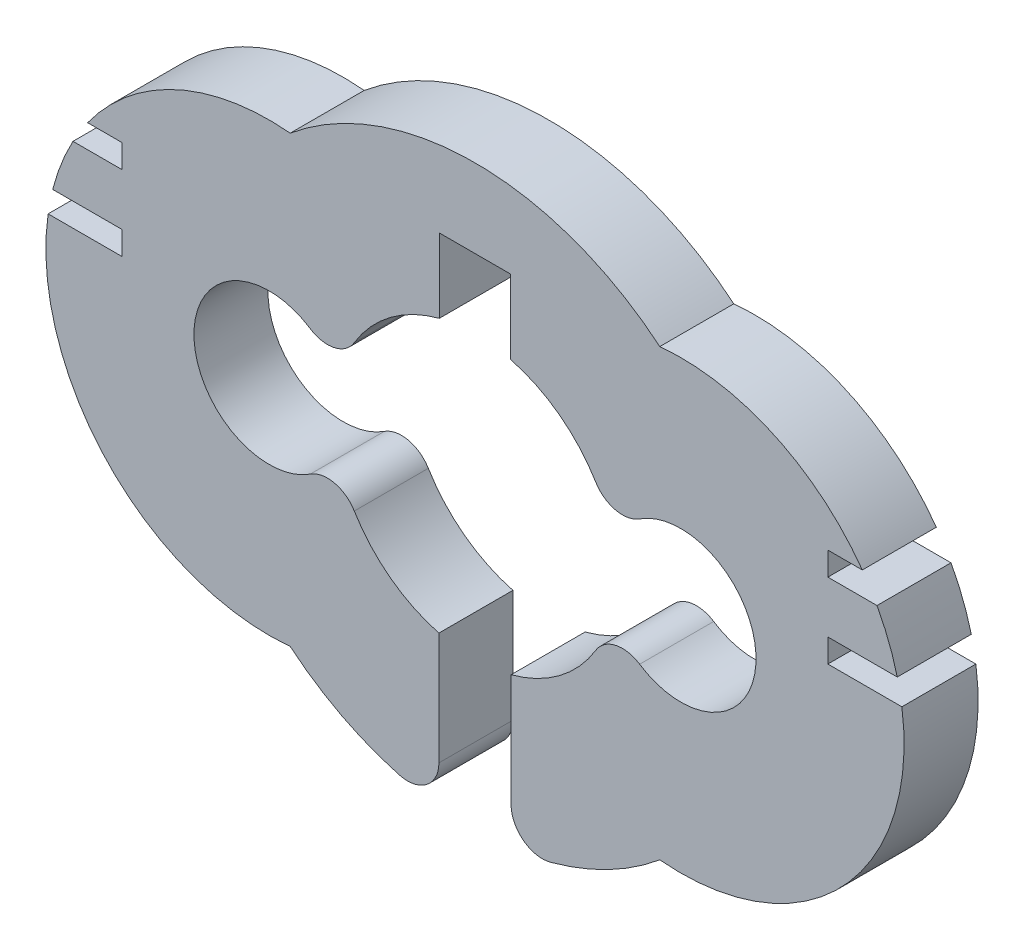
SolidWorks part; units mm, degrees
material "Acrylic (Medium-high impact)"
ref_plane "Front Plane" through (0, 0, 0) normal (0, 0, 1) x (1, 0, 0)
ref_plane "Top Plane" through (0, 0, 0) normal (0, 1, 0) x (1, 0, 0)
ref_plane "Right Plane" through (0, 0, 0) normal (1, 0, 0) x (0, 0, -1)
sketch "스케치1" plane through (0, 0, 0) normal (0, 0, 1) x (1, 0, 0)
  line L0 (0, 10.85) -> (0, 0) construction
  line L5 (-5.5721, 1.27) -> (-5.5721, -1.27) construction
  line L6 (-1.4475, 8.5286) -> (1.4475, 8.5286)
  line L7 (0, 0) -> (0, -8.574) construction
  line L8 (-1.4625, -11.6234) -> (1.4625, -11.6234) construction
  line L9 (-1.4625, -11.6234) -> (-1.4625, -5.5247)
  line L10 (-1.4625, -5.5247) -> (1.4625, -5.5247) construction
  line L11 (1.4625, -11.6234) -> (1.4625, -5.5247)
  line L12 (-1.4625, -11.6234) -> (1.4625, -5.5247) construction
  line L13 (-1.4625, -5.5247) -> (1.4625, -11.6234) construction
  line L14 (-1.4475, 8.5286) -> (-1.4475, 5.5286)
  line L15 (-1.4475, 5.5286) -> (1.4475, 5.5286) construction
  line L16 (1.4475, 8.5286) -> (1.4475, 5.5286)
  line L17 (-1.4475, 8.5286) -> (1.4475, 5.5286) construction
  line L18 (-1.4475, 5.5286) -> (1.4475, 8.5286) construction
  line L19 (-5.5721, 0) -> (0, 0) construction
  circle A0 centre (0, 0) radius 11.715 construction
  circle A1 centre (0, 0) radius 5.715 construction
  arc A2 (-1.4625, -11.6234) -> (1.4625, -11.6234) centre (0, 0) cw construction
  arc A3 (1.4625, -5.5247) -> (1.4475, 5.5286) centre (0, 0) ccw construction
  arc A4 (-1.4475, 5.5286) -> (-1.4625, -5.5247) centre (0, 0) ccw construction
  arc A5 (-7.4901, 9.0077) -> (-7.4901, -9.0077) centre (-8.3429, 0) ccw
  arc A6 (-5.5721, 1.27) -> (-5.5721, -1.27) centre (-8.3429, 0) ccw construction
  arc A7 (-5.5721, 1.27) -> (-5.5721, -1.27) centre (-8.3429, 0) ccw
  arc A8 (-5.5721, 1.27) -> (-1.4475, 5.5286) centre (0, 0) cw
  arc A9 (-5.5721, -1.27) -> (-1.4625, -5.5247) centre (0, 0) ccw
  arc A10 (-7.4901, -9.0077) -> (-1.4625, -11.6234) centre (0, 0) ccw
  arc A11 (5.5721, 1.27) -> (1.4475, 5.5286) centre (0, 0) ccw
  arc A12 (5.5721, -1.27) -> (1.4625, -5.5247) centre (0, 0) cw
  arc A13 (5.5721, 1.27) -> (5.5721, -1.27) centre (8.3429, 0) cw
  arc A14 (7.4901, -9.0077) -> (1.4625, -11.6234) centre (0, 0) cw
  arc A15 (7.4901, 9.0077) -> (7.4901, -9.0077) centre (8.3429, 0) cw
  arc A16 (-7.4901, 9.0077) -> (7.4901, 9.0077) centre (0, 0) cw
  point P2 (0, 10.85)
  point P5 (0, 7.0286)
  point P10 (0, -8.574)
  dimension "D1" = 6
  dimension "D2" = 11.43
  dimension "D6" = 6
  dimension "D7" = 3.048
  dimension "D3" = 2.895
  dimension "D4" = 3
  dimension "D5" = 2.925
  dimension "D8" = 2.54
extrude "보스-돌출1" add sketch "스케치1" along normal blind 3
sketch "스케치2" plane through (0, 0, 3) normal (0, 0, 1) x (1, 0, 0)
  line L0 (0, 0) -> (-11.3909, 0) construction
  line L1 (-17.3013, 1.27) -> (-14.3013, 1.27) construction
  line L2 (-17.3013, 1.27) -> (-17.3013, 5.27) construction
  line L3 (-17.3013, 5.27) -> (-14.3013, 5.27) construction
  line L4 (-14.3013, 1.27) -> (-14.3013, 5.27) construction
  line L5 (-17.3013, 1.27) -> (-14.3013, 5.27) construction
  line L6 (-17.3013, 5.27) -> (-14.3013, 1.27) construction
  line L7 (0, 0) -> (0, 11.715) construction
  line L8 (17.3013, 5.27) -> (14.3013, 5.27) construction
  line L9 (17.3013, 1.27) -> (17.3013, 5.27) construction
  line L10 (17.3013, 1.27) -> (14.3013, 1.27) construction
  line L11 (14.3013, 1.27) -> (14.3013, 5.27) construction
  line L12 (17.3013, 1.27) -> (14.3013, 1.27)
  line L13 (-17.3013, 5.27) -> (-14.3013, 5.27)
  line L14 (-17.3013, 5.27) -> (-17.3013, 4.32)
  line L15 (-17.3013, 4.32) -> (-14.3013, 4.32)
  line L16 (-14.3013, 5.27) -> (-14.3013, 4.32)
  line L17 (-17.3013, 5.27) -> (-14.3013, 4.32) construction
  line L18 (-17.3013, 4.32) -> (-14.3013, 5.27) construction
  line L19 (-17.3013, 2.22) -> (-14.3013, 2.22)
  line L20 (-17.3013, 2.22) -> (-17.3013, 1.27)
  line L21 (-17.3013, 1.27) -> (-14.3013, 1.27)
  line L22 (-14.3013, 2.22) -> (-14.3013, 1.27)
  line L23 (-17.3013, 2.22) -> (-14.3013, 1.27) construction
  line L24 (-17.3013, 1.27) -> (-14.3013, 2.22) construction
  line L25 (14.3013, 2.22) -> (14.3013, 1.27)
  line L26 (17.3013, 2.22) -> (14.3013, 2.22)
  line L27 (17.3013, 2.22) -> (17.3013, 1.27)
  line L28 (17.3013, 4.32) -> (14.3013, 4.32)
  line L29 (14.3013, 5.27) -> (14.3013, 4.32)
  line L30 (17.3013, 5.27) -> (14.3013, 5.27)
  line L31 (17.3013, 5.27) -> (17.3013, 4.32)
  arc A1 (7.4901, 9.0077) -> (-7.4901, 9.0077) centre (0, 0) ccw construction
  arc A2 (-5.5721, 1.27) -> (-5.5721, -1.27) centre (-8.3429, 0) ccw construction
  arc A3 (-7.4901, 9.0077) -> (-7.4901, -9.0077) centre (-8.3429, 0) ccw construction
  point P0 (-15.8013, 3.27)
  point P25 (-15.8013, 4.795)
  point P30 (-15.8013, 1.745)
  dimension "D1" = 3
  dimension "D2" = 1.27
  dimension "D3" = 4
  dimension "D4" = 0.95
extrude "컷-돌출1" cut sketch "스케치2" against normal up to surface (3 mm away) up to face at (0, -0.2706, 0)
fillet "필렛1" radius 1.27 6 edges at (1.4625, -11.6234, 1.5) (-1.4625, -11.6234, 1.5) (-5.5721, -1.27, 1.5) (5.5721, -1.27, 1.5) (5.5721, 1.27, 1.5) (-5.5721, 1.27, 1.5)
